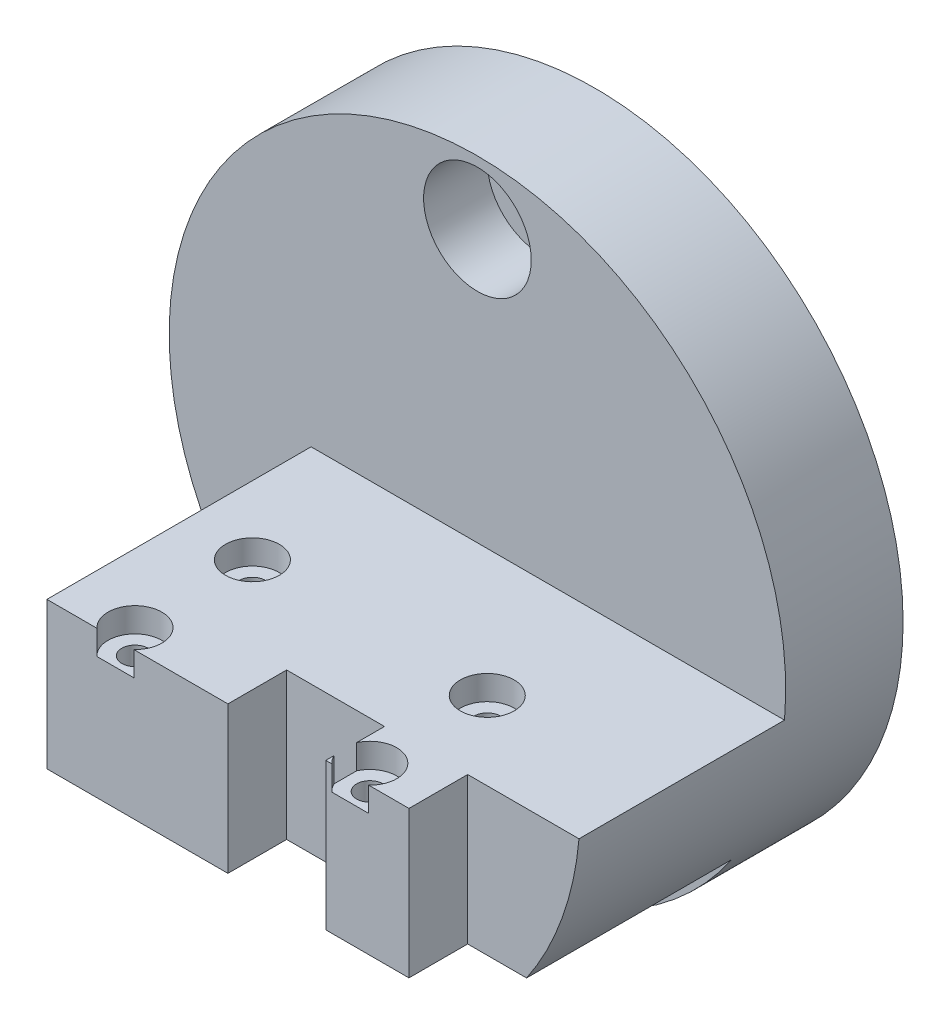
SolidWorks part; units mm, degrees
ref_plane "Front Plane" through (0, 0, 0) normal (0, 0, 1) x (1, 0, 0)
ref_plane "Top Plane" through (0, 0, 0) normal (0, 1, 0) x (1, 0, 0)
ref_plane "Right Plane" through (0, 0, 0) normal (1, 0, 0) x (0, 0, -1)
sketch "Sketch1" plane through (0, 0, 0) normal (0, 0, 1) x (1, 0, 0)
  line L0 (0, 0) -> (-17.6777, 17.6777) construction
  line L1 (0, 0) -> (0, 25) construction
  circle A0 centre (0, 0) radius 31.5
  circle A1 centre (0, 0) radius 25 construction
  dimension "D1" = 63
  dimension "D2" = 50
  dimension "D3" = 45
sketch "Sketch2" plane through (0, 0, 0) normal (0, 0, 1) x (1, 0, 0)
  circle A0 centre (0, 0) radius 31.5 construction
  circle A1 centre (0, 0) radius 31.5
extrude "Boss-Extrude1" add sketch "Sketch2" along normal blind 12
hole_wizard "CBORE for M6 SHCS1" positions "Sketch3" profile "Sketch4" counterbore size "M6" standard "ANSI Metric" end condition through all
sketch "Sketch3" plane through (0, 0, 12) normal (0, 0, 1) x (1, 0, 0)
  circle A0 centre (0, 0) radius 25 construction
  point P0 (0, 25)
  point P3 (0, -25)
sketch "Sketch4" plane through (0, 25, 12) normal (1, 0, 0) x (0, -1, 0)
  line L0 (0, 0) -> (0, 12)
  line L1 (0, 12) -> (3.3, 12)
  line L3 (3.3, 12) -> (3.3, 6.5)
  line L4 (3.3, 6.5) -> (5.5, 6.5)
  line L5 (5.5, 6.5) -> (5.5, 0)
  line L7 (5.5, 0) -> (0, 0)
  line L11 (0, -6.35) -> (0, 107.95) construction
  dimension "Thru Hole Dia." = 6.6
  dimension "Thru Hole Depth" = 12
  dimension "C'Bore Dia." = 11
  dimension "C'Bore Depth" = 6.5
sketch "Sketch5" plane through (0, 0, 0) normal (0, 0, -1) x (-1, 0, 0)
  circle A0 centre (17.6777, 17.6777) radius 3.15
  dimension "D1" = 6.3
extrude "Cut-Extrude1" cut sketch "Sketch5" against normal blind 6.5
sketch "Sketch6" plane through (0, 0, 12) normal (0, 0, -1) x (-1, 0, 0)
  line L0 (-31.3797, -2.75) -> (31.3797, -2.75)
  line L1 (-26.0228, -17.75) -> (26.0228, -17.75)
  circle A0 centre (0, 0) radius 31.5 construction
  arc A1 (-26.0228, -17.75) -> (-31.3797, -2.75) centre (0, 0) cw
  arc A2 (26.0228, -17.75) -> (31.3797, -2.75) centre (0, 0) ccw
  point P7 (-27.743, -14.919)
  point P9 (0, 0)
  point P10 (-31.3479, -3.0919)
  point P11 (31.3492, -3.079)
  point P12 (25.9018, -17.9262)
  dimension "D1" = 17.75
  dimension "D2" = 15
extrude "Boss-Extrude2" add sketch "Sketch6" against normal blind 27
hole_wizard "CBORE for M2.5 SHCS1" positions "Sketch7" profile "Sketch8" counterbore size "M2.5" standard "ANSI Metric" end condition through all
sketch "Sketch7" plane through (0, -2.75, 0) normal (0, 1, 0) x (1, 0, 0)
  line L1 (-9.9952, -25) -> (14.0048, -25) construction
  line L2 (-9.9952, -25) -> (-9.9952, -37) construction
  line L3 (-9.9952, -37) -> (14.0048, -37) construction
  line L4 (14.0048, -25) -> (14.0048, -37) construction
  line L5 (-9.9952, -31) -> (14.0048, -31) construction
  line L7 (2.0048, -25) -> (2.0048, -37) construction
  line L8 (31.3797, -39) -> (31.3797, -12) construction
  line L9 (-31.5, -12) -> (31.5, -12) construction
  point P1 (-9.9952, -25)
  point P2 (14.0048, -37)
  point P61 (-9.9952, -37)
  point P62 (14.0048, -25)
  dimension "D1" = 12
  dimension "D2" = 24
  dimension "D3" = 29.3749
  dimension "D4" = 13
sketch "Sketch8" plane through (-9.9952, -2.75, 25) normal (1, 0, 0) x (0, 0, 1)
  line L0 (0, 0) -> (0, 28.75)
  line L1 (0, 28.75) -> (1.35, 28.75)
  line L3 (1.35, 28.75) -> (1.35, 2.5)
  line L4 (1.35, 2.5) -> (2.75, 2.5)
  line L5 (2.75, 2.5) -> (2.75, 0)
  line L7 (2.75, 0) -> (0, 0)
  line L11 (0, -6.35) -> (0, 107.95) construction
  dimension "Thru Hole Dia." = 2.7
  dimension "Thru Hole Depth" = 28.75
  dimension "C'Bore Dia." = 5.5
  dimension "C'Bore Depth" = 2.5
sketch "Sketch9" plane through (0, -2.75, 0) normal (0, 1, 0) x (1, 0, 0)
  line L0 (-31.3797, -39) -> (-11.8827, -39) construction
  line L1 (-31.3797, -12) -> (-16.9952, -12)
  line L2 (-31.3797, -12) -> (-31.3797, -39)
  line L3 (-31.3797, -39) -> (-16.9952, -39)
  line L4 (-16.9952, -12) -> (-16.9952, -39)
  line L5 (31.3797, -39) -> (31.3797, -12) construction
  line L6 (1.5048, -39) -> (11.5048, -39)
  line L7 (1.5048, -39) -> (1.5048, -33)
  line L8 (1.5048, -33) -> (11.5048, -33)
  line L9 (11.5048, -39) -> (11.5048, -33)
  line L10 (20.0048, -39) -> (31.3797, -39)
  line L11 (20.0048, -39) -> (20.0048, -33)
  line L12 (20.0048, -33) -> (31.3797, -33)
  line L13 (31.3797, -39) -> (31.3797, -33)
  circle A0 centre (-9.9952, -37) radius 1.35 construction
  circle A1 centre (14.0048, -37) radius 1.35 construction
  dimension "D1" = 7
  dimension "D2" = 2.5
  dimension "D3" = 10
  dimension "D4" = 6
  dimension "D5" = 6
extrude "Cut-Extrude2" cut sketch "Sketch9" against normal blind 15
